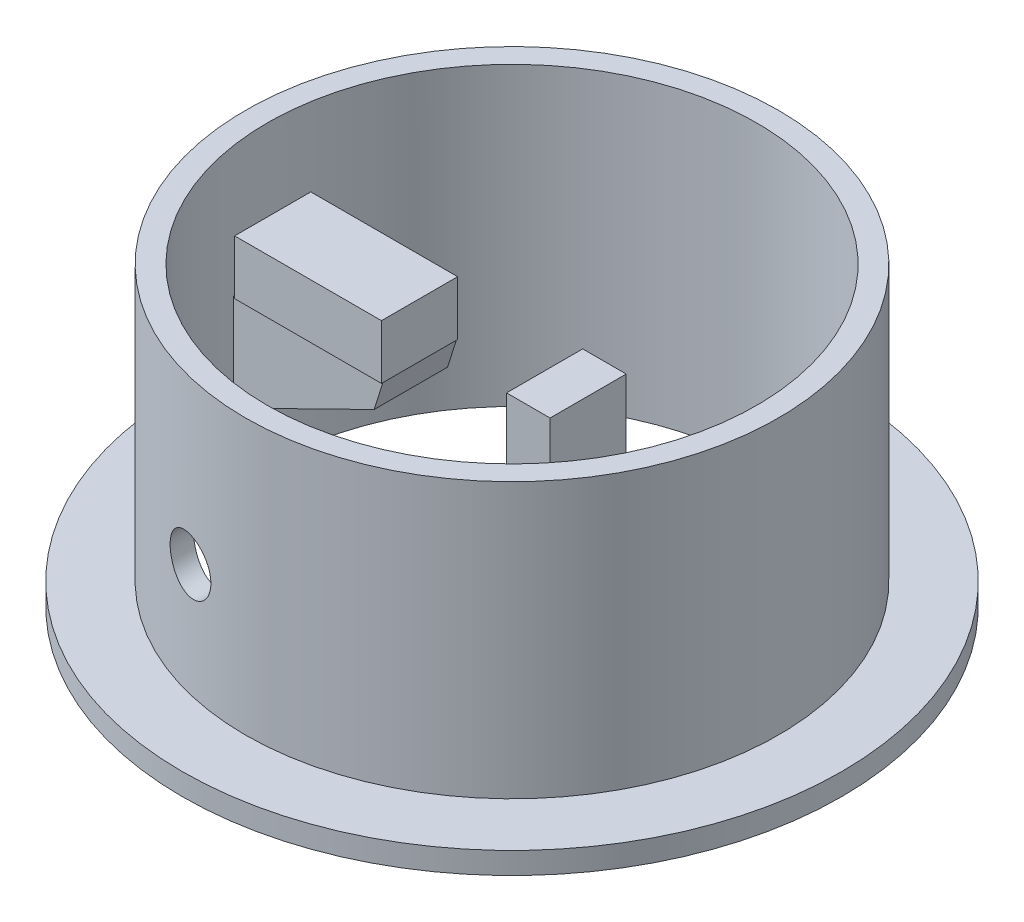
SolidWorks part; units mm, degrees
ref_plane "Front Plane" through (0, 0, 0) normal (0, 0, 1) x (1, 0, 0)
ref_plane "Top Plane" through (0, 0, 0) normal (0, 1, 0) x (1, 0, 0)
ref_plane "Right Plane" through (0, 0, 0) normal (1, 0, 0) x (0, 0, -1)
sketch "Sketch1" plane through (0, 0, 0) normal (0, 1, 0) x (1, 0, 0)
  circle A0 centre (0, 0) radius 60.625
  circle A1 centre (0, 0) radius 45
  dimension "D1" = 121.25
  dimension "D2" = 90
extrude "Boss-Extrude1" add sketch "Sketch1" along normal blind 4 contours A0
sketch "Sketch2" plane through (0, 4, 0) normal (0, 1, 0) x (1, 0, 0)
  circle A0 centre (0, 0) radius 45 construction
  circle A1 centre (0, 0) radius 45
  circle A2 centre (0, 0) radius 49
  dimension "D1" = 4
extrude "Boss-Extrude2" add sketch "Sketch2" along normal blind 50.5
ref_plane "Plane1" through (0, 34.5, 0) normal (0, 1, 0) x (1, 0, 0)
sketch "Sketch4" plane through (0, 0, 0) normal (0, 0, 1) x (1, 0, 0)
  line L0 (-60.625, 0) -> (60.625, 0) construction
  line L1 (6, 40.5) -> (14, 40.5)
  line L2 (6, 40.5) -> (6, 0)
  line L3 (6, 0) -> (14, 0)
  line L4 (14, 40.5) -> (14, 0)
  line L5 (49, 54.5) -> (-49, 54.5) construction
  line L6 (-45, 54.5) -> (-45, 4)
  line L7 (-17, 40.5) -> (-44, 40.5)
  line L8 (-17, 40.5) -> (-17, 30.5)
  line L9 (-17, 30.5) -> (-44, 30.5)
  line L10 (-44, 40.5) -> (-44, 30.5)
  line L11 (60.625, 4) -> (-60.625, 4) construction
  line L12 (-17, 30.5) -> (-45, 2.5)
  dimension "D1" = 6
  dimension "D2" = 8
  dimension "D3" = 14
  dimension "D4" = 23
  dimension "D5" = 27
  dimension "D6" = 10
  dimension "D7" = 45
  dimension "D8" = 14
extrude "Boss-Extrude4" add sketch "Sketch4" along normal mid plane 14 contours L9 L8 L7 L6 | L12 L9 L6 | L1 L4 L3 L2
sketch "Sketch5" plane through (0, 0, 0.8324) normal (0, -1, 0) x (1, 0, 0)
  line L0 (0.9227, 14.5796) -> (36.1058, 30.1379)
  line L1 (0.9227, -16.0291) -> (36.6512, -32.9046)
  line L2 (0.9227, 14.5796) -> (0.9227, -16.0291)
  arc A1 (36.6512, -32.9046) -> (36.1058, 30.1379) centre (-2.8733, -1.7229) ccw
extrude "Boss-Extrude5" add sketch "Sketch5" against normal up to surface (4 mm away) contours L0 A1 L1 L2 up to face at (0, 4, 60.625)
sketch "Sketch6" plane through (0, 0, 0) normal (0, 0, 1) x (1, 0, 0)
  circle A0 centre (-11.8474, 24.4856) radius 5
extrude "Cut-Extrude2" cut sketch "Sketch6" along normal blind 52 contours A0
sketch "Sketch11" plane through (0, 4, 0) normal (0, 1, 0) x (1, 0, 0)
  line L0 (16.2655, 12.7324) -> (16.2655, -6.5497)
  line L1 (16.2655, -6.5497) -> (5.715, -6.5497)
  line L2 (5.715, -6.5497) -> (5.715, -11.643)
  line L3 (5.715, -11.643) -> (30.818, -22.5574)
  line L4 (16.2655, 12.7324) -> (32.152, 20.615)
  arc A0 (32.152, 20.615) -> (30.818, -22.5574) centre (5.8984, -0.1806) cw
extrude "Cut-Extrude6" cut sketch "Sketch11" against normal through all
sketch "Sketch17" plane through (0, 0, 0) normal (0, 0, 1) x (1, 0, 0)
  line L0 (-17, 30.5) -> (-45, 30.5)
  line L1 (-45, 54.5) -> (-45, 0) construction
  line L2 (-45, 30.5) -> (-45, 12.4458)
  line L3 (-45, 12.4458) -> (-18.5901, 25.4335)
  line L4 (-18.5901, 25.4335) -> (-17, 30.5)
extrude "Boss-Extrude6" add sketch "Sketch17" along normal mid plane 13.5
